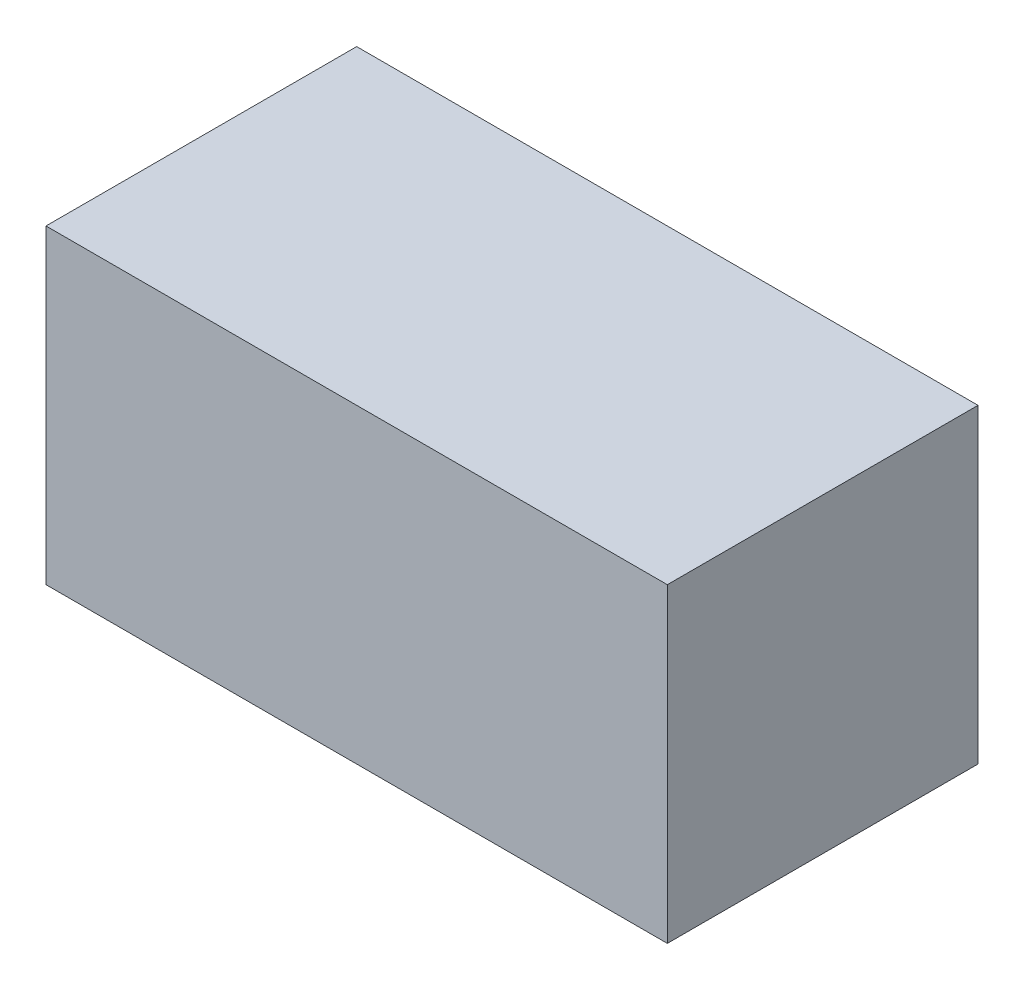
SolidWorks part; units mm, degrees
ref_plane "Front Plane" through (0, 0, 0) normal (0, 0, 1) x (1, 0, 0)
ref_plane "Top Plane" through (0, 0, 0) normal (0, 1, 0) x (1, 0, 0)
ref_plane "Right Plane" through (0, 0, 0) normal (1, 0, 0) x (0, 0, -1)
sketch "Sketch1" plane through (0, 0, 0) normal (0, 0, 1) x (1, 0, 0)
  line L1 (0, 0) -> (9.5, 0)
  line L2 (0, 0) -> (0, 4.75)
  line L3 (0, 4.75) -> (9.5, 4.75)
  line L4 (9.5, 0) -> (9.5, 4.75)
  dimension "D1" = 4.75
  dimension "D2" = 9.5
extrude "Boss-Extrude1" add sketch "Sketch1" along normal blind 4.75
